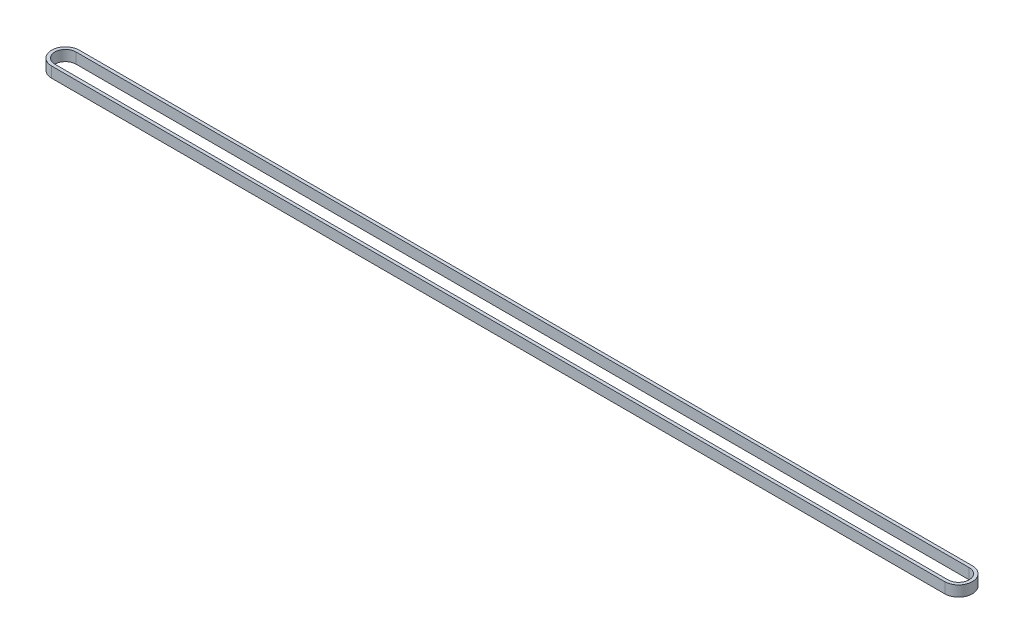
SolidWorks part; units mm, degrees
ref_plane "Front" through (0, 0, 0) normal (0, 0, 1) x (1, 0, 0)
ref_plane "Top" through (0, 0, 0) normal (0, 1, 0) x (1, 0, 0)
ref_plane "Right" through (0, 0, 0) normal (1, 0, 0) x (0, 0, -1)
sketch "Sketch1" plane through (0, 0, 0) normal (0, 1, 0) x (1, 0, 0)
  line L0 (0, 0) -> (505.5, 0) construction
  line L1 (0, 7.8) -> (505.5, 7.8)
  line L2 (0, 6) -> (505.5, 6)
  line L3 (0, -6) -> (505.5, -6)
  line L4 (0, -7.8) -> (505.5, -7.8)
  arc A4 (0, 6) -> (0, -6) centre (0, 0) ccw
  arc A5 (505.5, -6) -> (505.5, 6) centre (505.5, 0) ccw
  arc A6 (505.5, -7.8) -> (505.5, 7.8) centre (505.5, 0) ccw
  arc A7 (0, 7.8) -> (0, -7.8) centre (0, 0) ccw
  point P5 (252.75, 0)
  dimension "D1" = 6
  dimension "D2" = 505.5
  dimension "D3" = 1.8
extrude "Boss-Extrude1" add sketch "Sketch1" along normal blind 6
